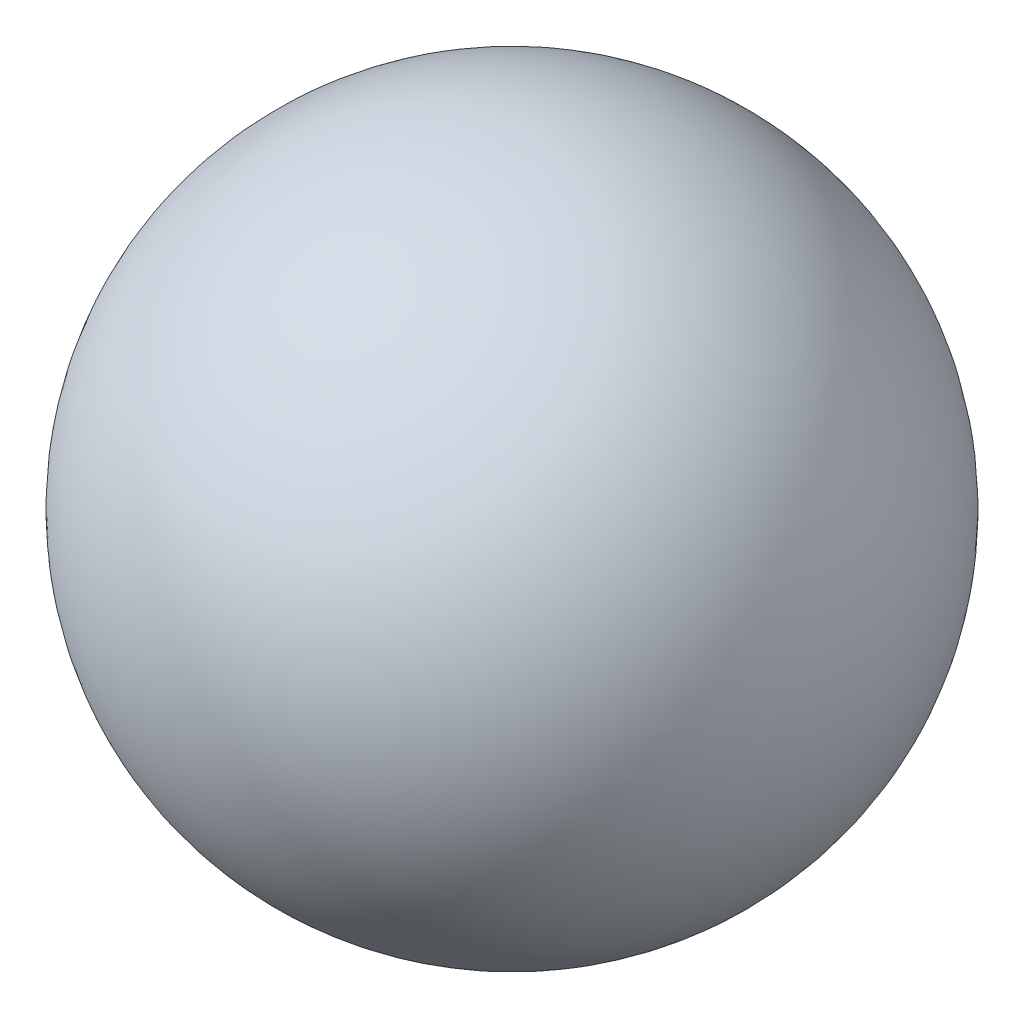
SolidWorks part; units mm, degrees
material "炭素鋼(普通)"
ref_plane "正面" through (0, 0, 0) normal (0, 0, 1) x (1, 0, 0)
ref_plane "平面" through (0, 0, 0) normal (0, 1, 0) x (1, 0, 0)
ref_plane "右側面" through (0, 0, 0) normal (1, 0, 0) x (0, 0, -1)
sketch "ｽｹｯﾁ1" plane through (0, 0, 0) normal (0, 0, 1) x (1, 0, 0)
  line L0 (1.6588, 49.9725) -> (0, -50)
  arc A0 (1.6588, 49.9725) -> (0, -50) centre (0, 0) ccw
revolve "回転1" add sketch "ｽｹｯﾁ1" angle 360 about L0
